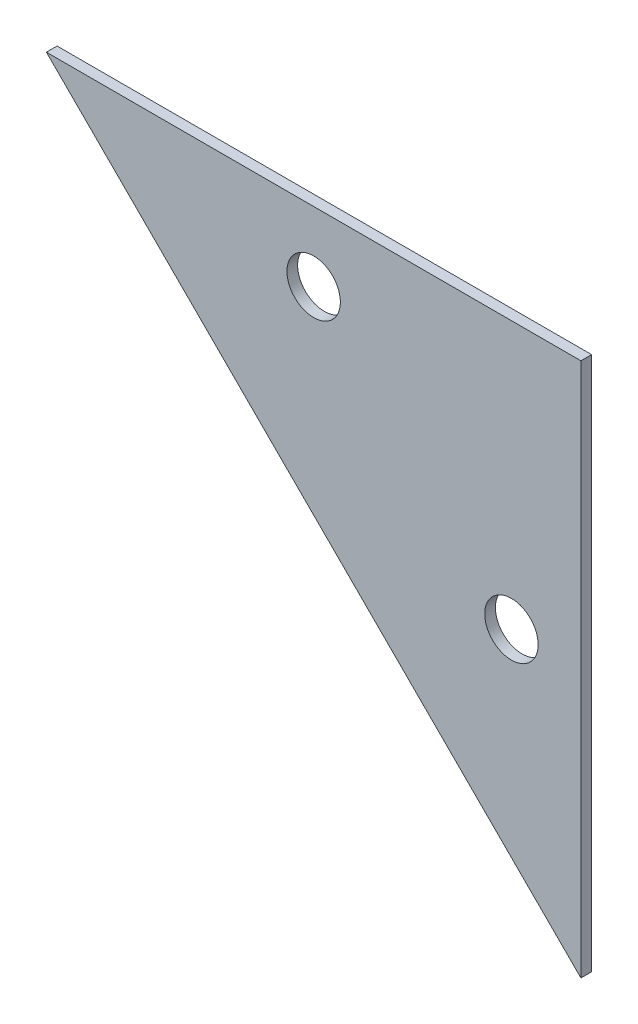
SolidWorks part; units mm, degrees
ref_plane "Płaszczyzna przednia" through (0, 0, 0) normal (0, 0, 1) x (1, 0, 0)
ref_plane "Płaszczyzna górna" through (0, 0, 0) normal (0, 1, 0) x (1, 0, 0)
ref_plane "Płaszczyzna prawa" through (0, 0, 0) normal (1, 0, 0) x (0, 0, -1)
sketch "Szkic1" plane through (0, 0, 0) normal (0, 0, 1) x (1, 0, 0)
  line L0 (0, 0) -> (0, -100)
  line L1 (0, -100) -> (-100, 0)
  line L2 (-100, 0) -> (0, 0)
  circle A0 centre (-50, -13) radius 5
  circle A1 centre (-13, -50) radius 5
  dimension "D2" = 10
  dimension "D3" = 10
  dimension "D1" = 100
  dimension "D4" = 50
  dimension "D5" = 50
  dimension "D6" = 13
  dimension "D7" = 13
extrude "Dodanie-wyciągnięcie1" add sketch "Szkic1" along normal blind 2
